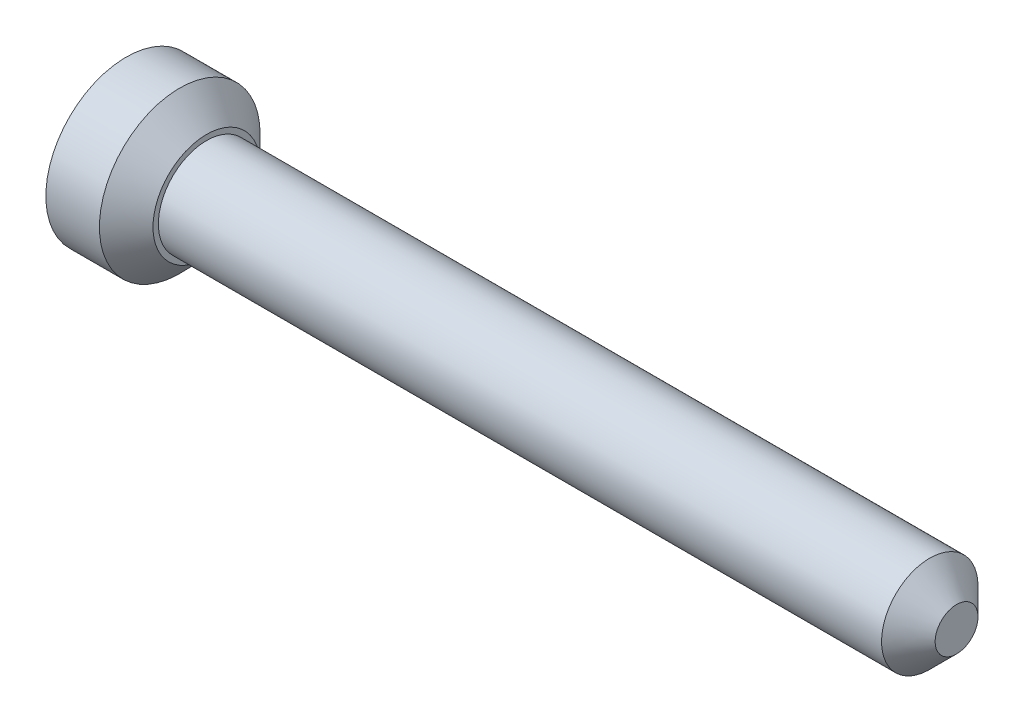
SolidWorks part; units mm, degrees
ref_plane "Спереди" through (0, 0, 0) normal (0, 0, 1) x (1, 0, 0)
ref_plane "Сверху" through (0, 0, 0) normal (0, 1, 0) x (1, 0, 0)
ref_plane "Справа" through (0, 0, 0) normal (1, 0, 0) x (0, 0, -1)
sketch "Sketch1" plane through (0, 0, 0) normal (1, 0, 0) x (0, 0, -1)
  circle A0 centre (0, 0) radius 0.9
  dimension "D1" = 1.8
extrude "Boss-Extrude1" add sketch "Sketch1" along normal blind 14 contours A0
sketch "Sketch2" plane through (0, 0, 0) normal (1, 0, 0) x (0, 0, -1)
  circle A0 centre (0, 0) radius 1.5
  dimension "D1" = 3
extrude "Boss-Extrude2" add sketch "Sketch2" against normal blind 1.5
chamfer "Chamfer1" distance 0.5 angle 45 2 edges at (14, 0, -0.9) (0, 0, -1.5)
